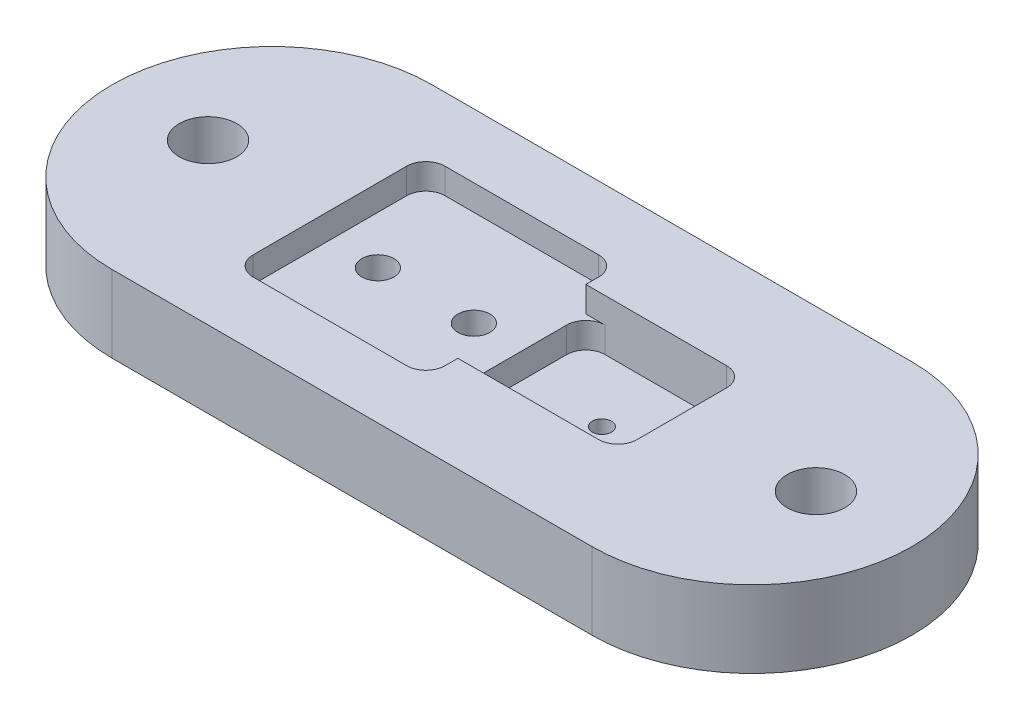
SolidWorks part; units mm, degrees
ref_plane "Front Plane" through (0, 0, 0) normal (0, 0, 1) x (1, 0, 0)
ref_plane "Top Plane" through (0, 0, 0) normal (0, 1, 0) x (1, 0, 0)
ref_plane "Right Plane" through (0, 0, 0) normal (1, 0, 0) x (0, 0, -1)
sketch "Sketch1" plane through (0, 0, 0) normal (0, 1, 0) x (1, 0, 0)
  line L1 (0, 0) -> (75, 0)
  line L2 (0, 0) -> (0, 50)
  line L3 (0, 50) -> (75, 50)
  line L4 (75, 0) -> (75, 50)
  arc A0 (75, 0) -> (75, 50) centre (75, 25) ccw
  arc A1 (0, 50) -> (0, 0) centre (0, 25) ccw
  dimension "D1" = 50
  dimension "D2" = 75
extrude "Boss-Extrude1" add sketch "Sketch1" along normal blind 12 contours L1 L4 L3 L2 | L4 A0 | L2 A1
sketch "Sketch2" plane through (0, 12, 0) normal (0, 1, 0) x (1, 0, 0)
  line L0 (-25, 25) -> (100, 25) construction
  line L1 (37.5, 50) -> (37.5, 0) construction
  line L2 (0, 50) -> (75, 50) construction
  line L3 (0, 0) -> (75, 0) construction
  circle A0 centre (-10, 25) radius 4.5
  arc A1 (0, 50) -> (0, 0) centre (0, 25) ccw construction
  arc A2 (75, 0) -> (75, 50) centre (75, 25) ccw construction
  circle A3 centre (85, 25) radius 4.5
  dimension "D1" = 9
  dimension "D2" = 15
extrude "Cut-Extrude1" cut sketch "Sketch2" against normal through all
sketch "Sketch3" plane through (0, 12, 0) normal (0, 1, 0) x (1, 0, 0)
  line L0 (-25, 25) -> (100, 25) construction
  line L1 (9.0414, 40) -> (39.0414, 40)
  line L2 (9.0414, 40) -> (9.0414, 10)
  line L3 (9.0414, 10) -> (39.0414, 10)
  line L4 (39.0414, 40) -> (39.0414, 10)
  arc A0 (0, 50) -> (0, 0) centre (0, 25) ccw construction
  arc A1 (75, 0) -> (75, 50) centre (75, 25) ccw construction
  point P12 (9.0414, 25)
  point P13 (0, 0)
  point P14 (0, 0)
  dimension "D1" = 30
  dimension "D2" = 30
extrude "Cut-Extrude2" cut sketch "Sketch3" against normal blind 4
sketch "Sketch4" plane through (0, 12, 0) normal (0, 1, 0) x (1, 0, 0)
  line L0 (-25, 25) -> (100, 25) construction
  line L1 (39.0414, 10) -> (39.0414, 40) construction
  line L2 (39.0414, 35) -> (64.0414, 35)
  line L3 (39.0414, 35) -> (39.0414, 15)
  line L4 (39.0414, 15) -> (64.0414, 15)
  line L5 (64.0414, 35) -> (64.0414, 15)
  arc A0 (0, 50) -> (0, 0) centre (0, 25) ccw construction
  arc A1 (75, 0) -> (75, 50) centre (75, 25) ccw construction
  point P14 (64.0414, 25)
  point P15 (0, 0)
  point P16 (0, 0)
  dimension "D1" = 20
  dimension "D2" = 25
extrude "Cut-Extrude3" cut sketch "Sketch4" against normal blind 8 contours L3 L2 L5 L4
fillet "Fillet1" radius 3 8 edges at (39.0414, 6, -35) (39.0414, 6, -15) (64.0414, 8, -15) (64.0414, 8, -35) (39.0414, 10, -10) (9.0414, 10, -10) (9.0414, 10, -40) (39.0414, 10, -40)
sketch "Sketch5" plane through (0, 4, 0) normal (0, 1, 0) x (1, 0, 0)
  line L0 (51.5414, 35) -> (51.5414, 15) construction
  line L1 (42.0414, 35) -> (61.0414, 35) construction
  line L2 (42.0414, 15) -> (61.0414, 15) construction
  circle A0 centre (51.5414, 25) radius 1.5
  point P8 (0, 0)
  point P9 (0, 0)
  dimension "D1" = 3
extrude "Cut-Extrude4" cut sketch "Sketch5" against normal through all
sketch "Sketch6" plane through (0, 8, 0) normal (0, 1, 0) x (1, 0, 0)
  line L0 (9.0414, 25) -> (24.0414, 25) construction
  line L1 (9.0414, 37) -> (9.0414, 13) construction
  line L2 (24.0414, 25) -> (39.0414, 25) construction
  line L3 (39.0414, 32) -> (39.0414, 18) construction
  circle A0 centre (16.5414, 25) radius 2.5
  circle A1 centre (31.5414, 25) radius 2.5
  point P8 (0, 0)
  point P10 (0, 0)
  point P13 (16.5414, 25)
  point P14 (14.9006, 25)
  point P15 (25.1379, 25)
  point P16 (39.0414, 25)
  point P17 (15.3015, 25)
  dimension "D1" = 5
extrude "Cut-Extrude5" cut sketch "Sketch6" against normal through all
